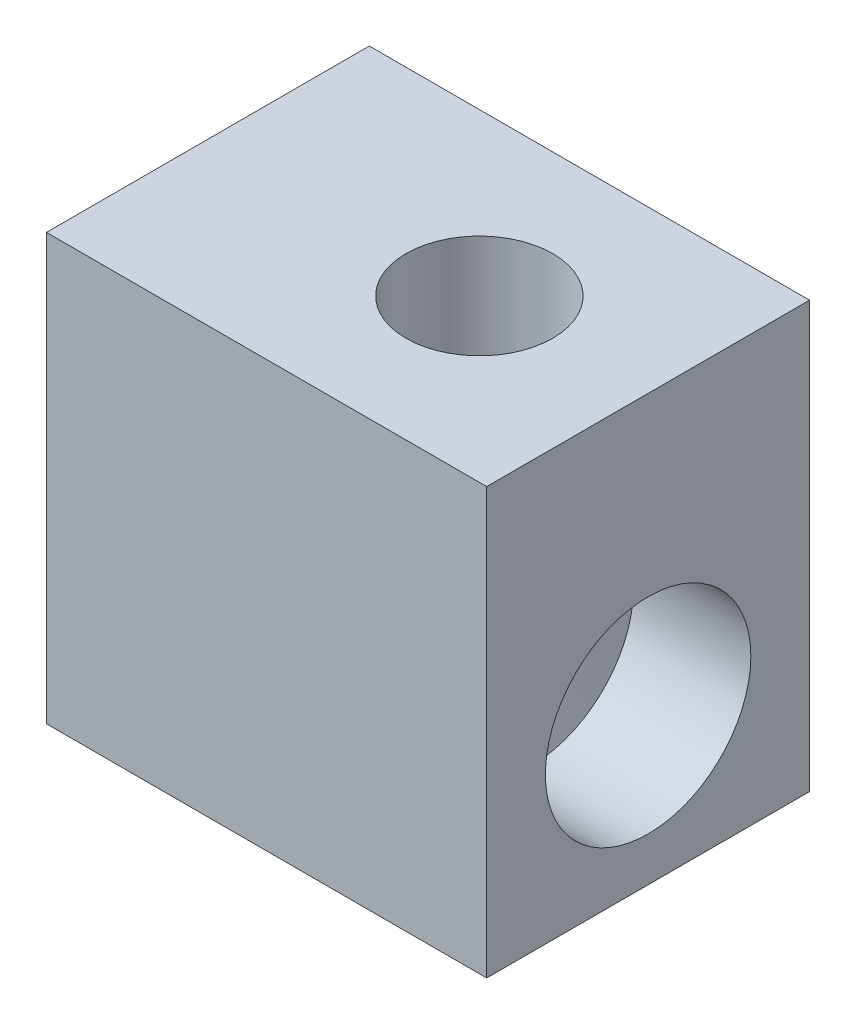
SolidWorks part; units mm, degrees
ref_plane "Plan de face" through (0, 0, 0) normal (0, 0, 1) x (1, 0, 0)
ref_plane "Plan de dessus" through (0, 0, 0) normal (0, 1, 0) x (1, 0, 0)
ref_plane "Plan de droite" through (0, 0, 0) normal (1, 0, 0) x (0, 0, -1)
sketch "Esquisse1" plane through (0, 0, 0) normal (0, 0, 1) x (1, 0, 0)
  line L1 (0, 0) -> (30, 0)
  line L2 (0, 0) -> (0, 29)
  line L3 (0, 29) -> (30, 29)
  line L4 (30, 0) -> (30, 29)
  dimension "D1" = 30
  dimension "D2" = 29
extrude "Boss.-Extru.1" add sketch "Esquisse1" along normal blind 22
sketch "Esquisse2" plane through (0, 0, 0) normal (-1, 0, 0) x (0, 0, 1)
  line L0 (11, 0) -> (11, 29) construction
  line L1 (22, 0) -> (0, 0) construction
  line L2 (22, 29) -> (0, 29) construction
  circle A0 centre (11, 10) radius 7
  dimension "D1" = 14
  dimension "D2" = 10
extrude "Enlèv. mat.-Extru.1" cut sketch "Esquisse2" against normal blind 8
sketch "Esquisse3" plane through (30, 0, 0) normal (1, 0, 0) x (0, 0, -1)
  line L0 (-11, 29) -> (-11, 0) construction
  line L1 (-22, 29) -> (0, 29) construction
  line L2 (-22, 0) -> (0, 0) construction
  circle A0 centre (-11, 10) radius 7
  dimension "D1" = 14
  dimension "D2" = 10
extrude "Enlèv. mat.-Extru.2" cut sketch "Esquisse3" against normal blind 8
ref_plane "Plan1" through (0, 10, 0) normal (0, 1, 0) x (1, 0, 0)
sketch "Esquisse4" plane through (0, 10, 0) normal (0, 1, 0) x (1, 0, 0)
  line L0 (0, -11) -> (30, -11) construction
  line L1 (0, -22) -> (0, 0) construction
  line L2 (30, -22) -> (30, 0) construction
  line L3 (30, -11) -> (21, -11) construction
  line L4 (0, -11) -> (9, -11) construction
  line L5 (9, -11) -> (13, -11) construction
  line L6 (21, -11) -> (16, -11) construction
  line L7 (9, -9) -> (9, -13) construction
  line L8 (9, -13) -> (13, -13) construction
  line L9 (13, -13) -> (13, -9) construction
  line L10 (13, -9) -> (9, -9) construction
  line L12 (9, -9) -> (12, -9)
  line L13 (12, -9) -> (13, -11)
  line L14 (13, -11) -> (9, -11)
  line L15 (16, -11) -> (17, -9)
  line L16 (17, -9) -> (21, -9)
  line L18 (21, -11) -> (16, -11)
  line L19 (9, -4) -> (9, -18) construction
  line L20 (9, -4) -> (21, -4) construction
  line L21 (21, -4) -> (21, -18) construction
  line L22 (21, -18) -> (9, -18) construction
  line L23 (9, -9) -> (8, -4)
  line L24 (8, -4) -> (8, -11)
  line L25 (8, -11) -> (9, -11)
  line L26 (21, -9) -> (21, -4)
  line L28 (22, -4) -> (21, -9)
  line L29 (21, -11) -> (22, -11)
  line L30 (22, -11) -> (22, -4)
  dimension "D1" = 9
  dimension "D2" = 9
  dimension "D3" = 4
  dimension "D4" = 5
  dimension "D5" = 4
  dimension "D6" = 2
  dimension "D7" = 3
  dimension "D8" = 4
  dimension "D9" = 2
  dimension "D10" = 14
  dimension "D11" = 7
  dimension "D12" = 1
  dimension "D13" = 1
  dimension "D14" = 7
  dimension "D15" = 7
revolve "Enlèvement de matière-Révolution3" cut sketch "Esquisse4" angle 360 about L0
sketch "Esquisse8" plane through (0, 29, 0) normal (0, 1, 0) x (1, 0, 0)
  line L0 (18.5, 0) -> (18.5, -22) construction
  line L1 (30, 0) -> (0, 0) construction
  line L2 (30, -22) -> (0, -22) construction
  line L3 (0, -22) -> (0, 0) construction
  circle A0 centre (18.5, -11) radius 5
  dimension "D2" = 10
  dimension "D1" = 18.5
extrude "Enlèv. mat.-Extru.3" cut sketch "Esquisse8" against normal blind 11
sketch "Esquisse9" plane through (0, 18, 0) normal (0, 1, 0) x (1, 0, 0)
  circle A0 centre (18.5, -11) radius 1.5
  dimension "D1" = 3
extrude "Enlèv. mat.-Extru.4" cut sketch "Esquisse9" against normal up to next
ref_plane "Plan3" through (0, 10, 0) normal (0, 1, 0) x (1, 0, 0)
sketch "Esquisse10" plane through (0, 10, 0) normal (0, 1, 0) x (1, 0, 0)
  line L0 (0, -11) -> (11, -11) construction
  line L1 (0, -22) -> (0, 0) construction
  circle A0 centre (11, -11) radius 1
  dimension "D1" = 11
ref_plane "Plan4" through (0, 0, 11) normal (0, 0, 1) x (1, 0, 0)
sketch "Esquisse11" plane through (0, 0, 11) normal (0, 0, 1) x (1, 0, 0)
  line L0 (11, 10) -> (11, 29) construction
  line L1 (12, 10) -> (10, 10) construction
  line L2 (30, 29) -> (0, 29) construction
  line L3 (13.5, 19.5) -> (11, 19.5) construction
  line L4 (13.5, 29) -> (13.5, 18) construction
  line L5 (11, 19.5) -> (12.5, 19.5) construction
  line L6 (11, 19.5) -> (11, 18) construction
  line L7 (12.5, 19.5) -> (13.5, 19.5)
  line L8 (11, 10) -> (11, 18)
  line L9 (13.5, 19.5) -> (13.7285, 19.5)
  arc A0 (11, 18) -> (12.5, 19.5) centre (12.5, 18) cw
  dimension "D1" = 1.5
  dimension "D2" = 1.5
  dimension "D3" = 1.5
sweep "Enlèvement de matière-Balayage1" cut profiles "Esquisse10" path "Esquisse11"
scale "Echelle1" scale about centroid uniform scaling yes scale factor 0.578571
